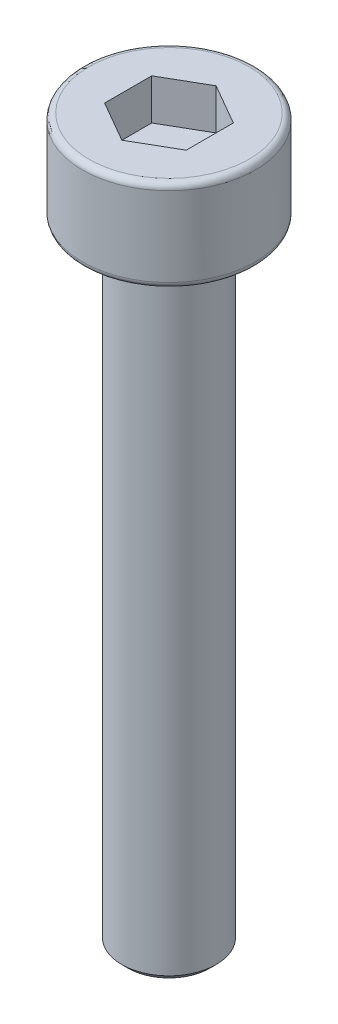
SolidWorks part; units mm, degrees
material "304不锈钢"
ref_plane "前视基准面" through (0, 0, 0) normal (0, 0, 1) x (1, 0, 0)
ref_plane "上视基准面" through (0, 0, 0) normal (0, 1, 0) x (1, 0, 0)
ref_plane "右视基准面" through (0, 0, 0) normal (1, 0, 0) x (0, 0, -1)
sketch "草图1" plane through (0, 0, 0) normal (0, 0, 1) x (1, 0, 0)
  line L0 (0, 0) -> (0, -21.235) construction
  line L1 (0, 0) -> (2.75, 0)
  line L2 (2.75, 0) -> (2.75, -2.93)
  line L3 (2.75, -2.93) -> (1.5, -2.93)
  line L4 (1.5, -2.93) -> (1.5, -22.93)
  line L5 (1.5, -22.93) -> (0, -22.93)
  line L6 (0, -22.93) -> (0, 0)
  point P5 (2.125, -2.93)
  dimension "D1" = 2.93
  dimension "D2" = 5.5
  dimension "D3" = 3
  dimension "D4" = 20
revolve "旋转1" add sketch "草图1" angle 360 about L0
cosmetic thread "装饰螺纹线1" parameters "D2"=2.459
sketch "草图2" plane through (0, 0, 0) normal (0, 1, 0) x (1, 0, 0)
  line L1 (0, 1.5) -> (-1.299, 0.75)
  line L2 (-1.299, 0.75) -> (-1.299, -0.75)
  line L3 (-1.299, -0.75) -> (0, -1.5)
  line L4 (0, -1.5) -> (1.299, -0.75)
  line L5 (1.299, -0.75) -> (1.299, 0.75)
  line L6 (1.299, 0.75) -> (0, 1.5)
  circle A0 centre (0, 0) radius 1.5 construction
  dimension "D1" = 3
extrude "切除-拉伸1" cut sketch "草图2" against normal blind 1.3
fillet "圆角1" radius 0.2 2 edges at (0, 0, 2.75) (0, -2.93, 2.75)
chamfer "倒角1" distance 0.2 angle 45 1 edges at (0, -22.93, 1.5)
